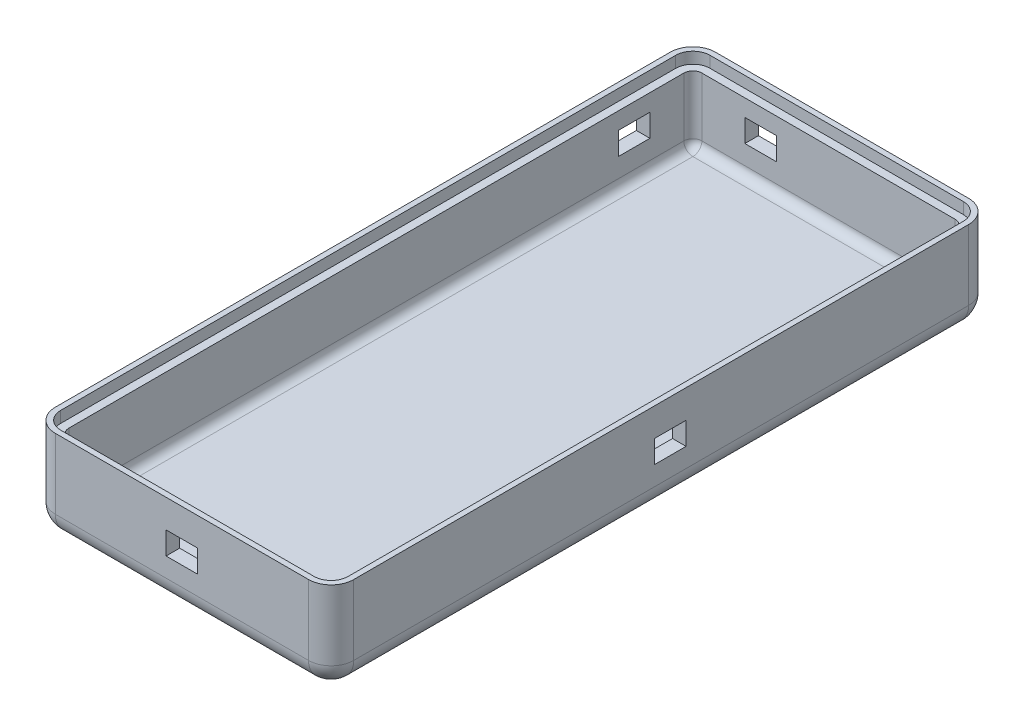
SolidWorks part; units mm, degrees
ref_plane "Plano frontal" through (0, 0, 0) normal (0, 0, 1) x (1, 0, 0)
ref_plane "Plano superior" through (0, 0, 0) normal (0, 1, 0) x (1, 0, 0)
ref_plane "Plano direito" through (0, 0, 0) normal (1, 0, 0) x (0, 0, -1)
sketch "Esboço1" plane through (0, 0, 0) normal (0, 1, 0) x (1, 0, 0)
  line L1 (30, -70) -> (-30, -70)
  line L2 (30, -70) -> (30, 70)
  line L3 (30, 70) -> (-30, 70)
  line L4 (-30, -70) -> (-30, 70)
  line L5 (30, -70) -> (-30, 70) construction
  line L6 (30, 70) -> (-30, -70) construction
  point P0 (0, 0)
  dimension "D1" = 140
  dimension "D2" = 60
extrude "Ressalto-extrusão1" add sketch "Esboço1" along normal blind 15
fillet "Filete1" radius 2 8 edges at (0, 0, -70) (-30, 7.5, -70) (-30, 0, 0) (30, 7.5, -70) (30, 0, 0) (30, 7.5, 70) (0, 0, 70) (-30, 7.5, 70)
shell "Casca1" thickness 3
sketch "Esboço3" plane through (0, 15, 0) normal (0, 1, 0) x (1, 0, 0)
  line L1 (-31.8, 68) -> (-31.8, -68)
  line L2 (-28, -71.8) -> (28, -71.8)
  line L3 (31.8, -68) -> (31.8, 68)
  line L13 (28, 71.8) -> (-28, 71.8)
  line L17 (28, 73) -> (-28, 73)
  line L18 (-33, 68) -> (-33, -68)
  line L19 (-28, -73) -> (28, -73)
  line L20 (33, -68) -> (33, 68)
  line L21 (28, 73) -> (-28, 73)
  line L22 (-33, 68) -> (-33, -68)
  line L23 (-28, -73) -> (28, -73)
  line L24 (33, -68) -> (33, 68)
  arc A16 (-28, 71.8) -> (-31.8, 68) centre (-28, 68) ccw
  arc A17 (-31.8, -68) -> (-28, -71.8) centre (-28, -68) ccw
  arc A18 (28, -71.8) -> (31.8, -68) centre (28, -68) ccw
  arc A19 (31.8, 68) -> (28, 71.8) centre (28, 68) ccw
  arc A20 (-28, 73) -> (-33, 68) centre (-28, 68) ccw
  arc A21 (-33, -68) -> (-28, -73) centre (-28, -68) ccw
  arc A22 (28, -73) -> (33, -68) centre (28, -68) ccw
  arc A23 (33, 68) -> (28, 73) centre (28, 68) ccw
  arc A24 (-28, 73) -> (-33, 68) centre (-28, 68) ccw
  arc A25 (-33, -68) -> (-28, -73) centre (-28, -68) ccw
  arc A26 (28, -73) -> (33, -68) centre (28, -68) ccw
  arc A27 (33, 68) -> (28, 73) centre (28, 68) ccw
  dimension "D1" = 0
  dimension "D2" = 1.2
extrude "Ressalto-extrusão2" add sketch "Esboço3" along normal blind 2.5
ref_plane "Plano5" through (0, 0, -25) normal (0, 0, 1) x (1, 0, 0)
sketch "Esboço4" plane through (-33, 0, 0) normal (-1, 0, 0) x (0, 0, 1)
  line L0 (-60.5, 11.25) -> (-53.5, 11.25)
  line L1 (-53.5, 11.25) -> (-53.5, 6.25)
  line L2 (-53.5, 6.25) -> (-60.5, 6.25)
  line L3 (-60.5, 6.25) -> (-60.5, 11.25)
  line L4 (-57, 11.25) -> (-57, 6.25) construction
  line L7 (0, 0) -> (0, 17.5) construction
  line L8 (-68, 17.5) -> (68, 17.5) construction
  line L9 (0, 0) -> (-74.6366, 0) construction
  dimension "D1" = 7
  dimension "D2" = 5
  dimension "D3" = 57
  dimension "D4" = 11.25
extrude "Corte-extrusão1" cut sketch "Esboço4" against normal up to next
sketch "Esboço5" plane through (0, 0, -73) normal (0, 0, -1) x (-1, 0, 0)
  line L0 (0, 0) -> (0, 17.5) construction
  line L1 (-28, 17.5) -> (28, 17.5) construction
  line L2 (0, 0) -> (34.3468, 0) construction
  line L3 (18.5, 6.25) -> (18.5, 11.25)
  line L4 (18.5, 11.25) -> (11.5, 11.25)
  line L5 (11.5, 11.25) -> (11.5, 6.25)
  line L6 (11.5, 6.25) -> (18.5, 6.25)
  line L7 (15, 6.25) -> (15, 11.25) construction
  dimension "D1" = 11.25
  dimension "D2" = 5
  dimension "D3" = 15
  dimension "D4" = 7
extrude "Corte-extrusão2" cut sketch "Esboço5" against normal up to next
sketch "Esboço6" plane through (33, 0, 0) normal (1, 0, 0) x (0, 0, -1)
  line L0 (0, 0) -> (0, 17.5) construction
  line L1 (-68, 17.5) -> (68, 17.5) construction
  line L2 (0, 0) -> (14.9932, 0) construction
  line L3 (5.5, 11.25) -> (-1.5, 11.25)
  line L4 (-1.5, 11.25) -> (-1.5, 6.25)
  line L5 (-1.5, 6.25) -> (5.5, 6.25)
  line L6 (5.5, 6.25) -> (5.5, 11.25)
  line L7 (2, 6.25) -> (2, 11.25) construction
  dimension "D1" = 11.25
  dimension "D2" = 7
  dimension "D3" = 5
  dimension "D4" = 2
extrude "Corte-extrusão3" cut sketch "Esboço6" against normal up to next
sketch "Esboço7" plane through (0, 0, 73) normal (0, 0, 1) x (1, 0, 0)
  line L0 (0, 0) -> (0, 17.5) construction
  line L1 (-28, 17.5) -> (28, 17.5) construction
  line L3 (-3.5, 11.25) -> (3.5, 11.25)
  line L4 (-3.5, 11.25) -> (-3.5, 6.25)
  line L5 (-3.5, 6.25) -> (3.5, 6.25)
  line L6 (3.5, 11.25) -> (3.5, 6.25)
  line L7 (-3.5, 11.25) -> (3.5, 6.25) construction
  line L8 (-3.5, 6.25) -> (3.5, 11.25) construction
  point P5 (0, 8.75)
  dimension "D1" = 11.25
  dimension "D2" = 7
  dimension "D3" = 5
extrude "Corte-extrusão4" cut sketch "Esboço7" against normal up to next
